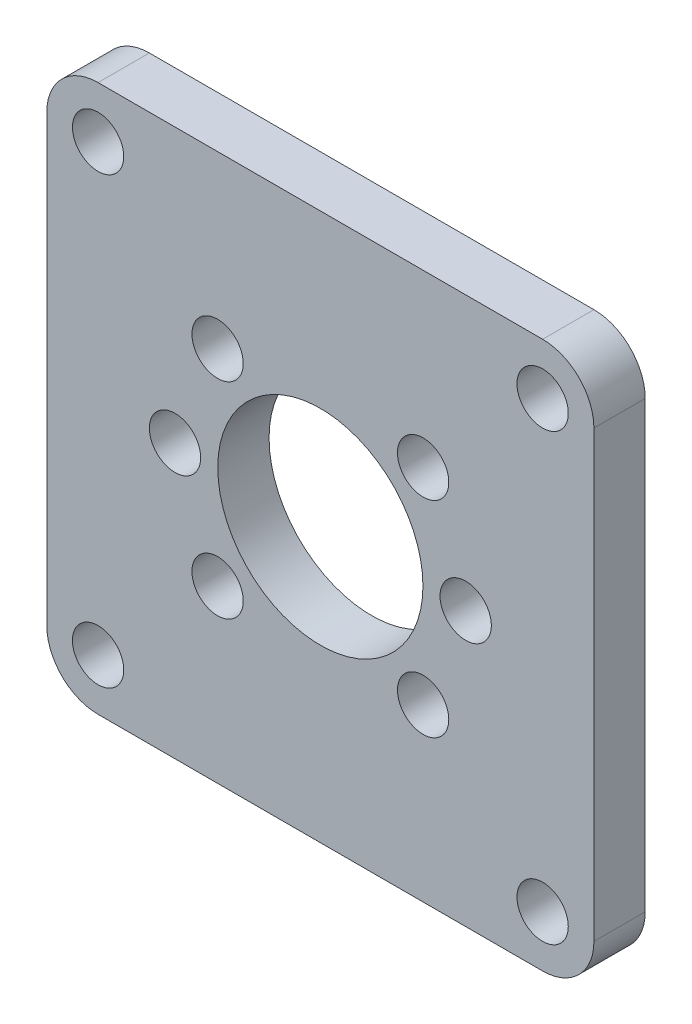
SolidWorks part; units mm, degrees
ref_plane "Plan de face" through (0, 0, 0) normal (0, 0, 1) x (1, 0, 0)
ref_plane "Plan de dessus" through (0, 0, 0) normal (0, 1, 0) x (1, 0, 0)
ref_plane "Plan de droite" through (0, 0, 0) normal (1, 0, 0) x (0, 0, -1)
sketch "Esquisse1" plane through (0, 0, 0) normal (0, 0, 1) x (1, 0, 0)
  line L1 (-13, -16) -> (13, -16)
  line L2 (-16, -13) -> (-16, 13)
  line L3 (-13, 16) -> (13, 16)
  line L4 (16, -13) -> (16, 13)
  line L5 (-16, -16) -> (16, 16) construction
  line L6 (-16, 16) -> (16, -16) construction
  arc A0 (-16, -13) -> (-13, -16) centre (-13, -13) ccw
  arc A1 (13, -16) -> (16, -13) centre (13, -13) ccw
  arc A2 (16, 13) -> (13, 16) centre (13, 13) ccw
  arc A3 (-13, 16) -> (-16, 13) centre (-13, 13) ccw
  point P0 (0, 0)
  dimension "D1" = 3
  dimension "D2" = 32
extrude "Boss.-Extru.1" add sketch "Esquisse1" along normal blind 3
sketch "Esquisse2" plane through (0, 0, 3) normal (0, 0, 1) x (1, 0, 0)
  line L0 (0, 0) -> (-16, 0) construction
  line L1 (-16, 13) -> (-16, -13) construction
  line L2 (0, 0) -> (-6.0104, 6.0104) construction
  line L3 (0, 0) -> (0, 16) construction
  line L4 (13, 16) -> (-13, 16) construction
  circle A0 centre (0, 0) radius 6
  circle A1 centre (0, 0) radius 8.5 construction
  circle A2 centre (-8.5, 0) radius 1.5
  circle A3 centre (-6.0104, 6.0104) radius 1.5
  circle A4 centre (-6.0104, -6.0104) radius 1.5
  circle A5 centre (6.0104, -6.0104) radius 1.5
  circle A6 centre (8.5, 0) radius 1.5
  circle A7 centre (6.0104, 6.0104) radius 1.5
  dimension "D1" = 12
  dimension "D2" = 17
  dimension "D3" = 3
  dimension "D4" = 45
extrude "Enlèv. mat.-Extru.1" cut sketch "Esquisse2" against normal through all
sketch "Esquisse3" plane through (0, 0, 3) normal (0, 0, 1) x (1, 0, 0)
  line L0 (0, 0) -> (0, 16) construction
  line L1 (13, 16) -> (-13, 16) construction
  line L2 (0, 0) -> (-16, 0) construction
  line L3 (-16, 13) -> (-16, -13) construction
  circle A0 centre (-13, 13) radius 1.5
  arc A4 (-13, 16) -> (-16, 13) centre (-13, 13) ccw construction
  circle A5 centre (13, 13) radius 1.5
  circle A6 centre (13, -13) radius 1.5
  circle A7 centre (-13, -13) radius 1.5
  dimension "D1" = 3
extrude "Enlèv. mat.-Extru.2" cut sketch "Esquisse3" against normal through all
